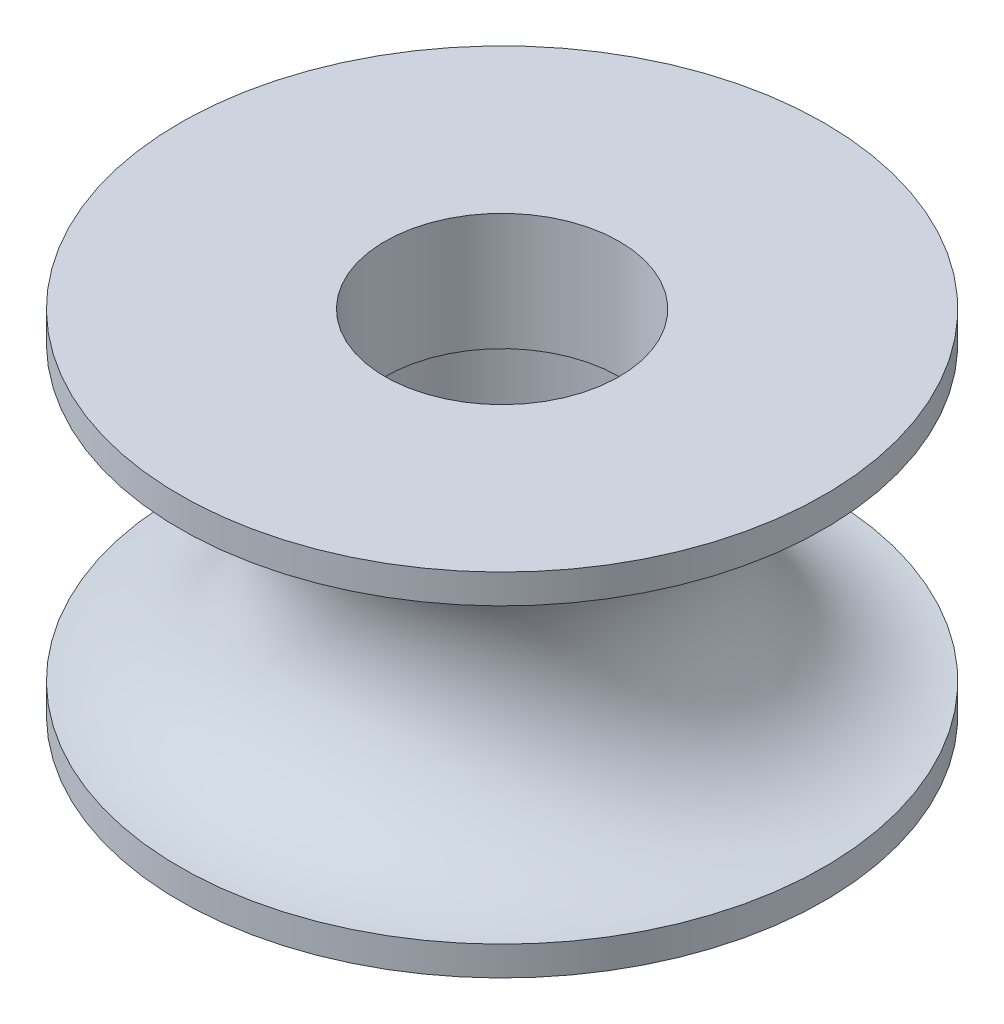
SolidWorks part; units mm, degrees
ref_plane "前视基准面" through (0, 0, 0) normal (0, 0, 1) x (1, 0, 0)
ref_plane "上视基准面" through (0, 0, 0) normal (0, 1, 0) x (1, 0, 0)
ref_plane "右视基准面" through (0, 0, 0) normal (1, 0, 0) x (0, 0, -1)
sketch "草图6" plane through (0, 0, 0) normal (0, 0, 1) x (1, 0, 0)
  line L0 (0, 0) -> (0, 17.1768) construction
sketch "草图7" plane through (0, 0, 0) normal (0, 0, 1) x (1, 0, 0)
  line L1 (-5, 5) -> (-5, -5)
  line L3 (0, -200000) -> (0, 200017.1768) construction
  line L4 (0, 0) -> (-53.5124, 0) construction
  line L5 (-11, 5) -> (-11, 0) construction
  line L6 (-11, 0) -> (-11, -5) construction
  line L7 (-11, 0) -> (-11, 5) construction
  line L8 (-11, 5) -> (-11, 6)
  line L9 (-11, 6) -> (-5, 6)
  line L10 (-5, 6) -> (-5, 5)
  line L11 (-11, -5) -> (-11, -6)
  line L12 (-11, -6) -> (-5, -6)
  line L13 (-5, -6) -> (-5, -5)
  circle A0 centre (-11, 0) radius 5 construction
  arc A1 (-11, 5) -> (-11, -5) centre (-11, 0) cw
  point P6 (-5, 0)
  dimension "D1" = 5
  dimension "D2" = 5
  dimension "D3" = 1
  dimension "D4" = 6
  dimension "D5" = 180
  dimension "D6" = 1
revolve "旋转1" add sketch "草图7" angle 360 about L0
sketch "草图8" plane through (0, 0, 0) normal (0, 1, 0) x (1, 0, 0)
  line L0 (0, 11) -> (0, -11) construction
  circle A0 centre (0, 0) radius 11 construction
sketch "草图9" plane through (0, 0, 0) normal (0, 0, 1) x (1, 0, 0)
  line L0 (-5, -6) -> (5, -6) construction
  line L1 (-5, 6) -> (-4, 6)
  line L2 (-5, 6) -> (-5, 2)
  line L3 (-5, -6) -> (-4, -6)
  line L4 (-4, 6) -> (-4, 2)
  line L5 (-5, 2) -> (-4, 2)
  line L6 (-5, -2) -> (-4, -2)
  line L7 (-5, -2) -> (-5, -6)
  line L8 (-4, -2) -> (-4, -6)
  dimension "D1" = 1
  dimension "D2" = 4
  dimension "D3" = 4
revolve "旋转2" add sketch "草图9" angle 360 about L0
sketch "草图10" plane through (0, -6, 0) normal (0, -1, 0) x (1, 0, 0)
  circle A0 centre (0, 0) radius 5.1
  dimension "D1" = 10.2
extrude "切除-拉伸2" cut sketch "草图10" against normal blind 8
